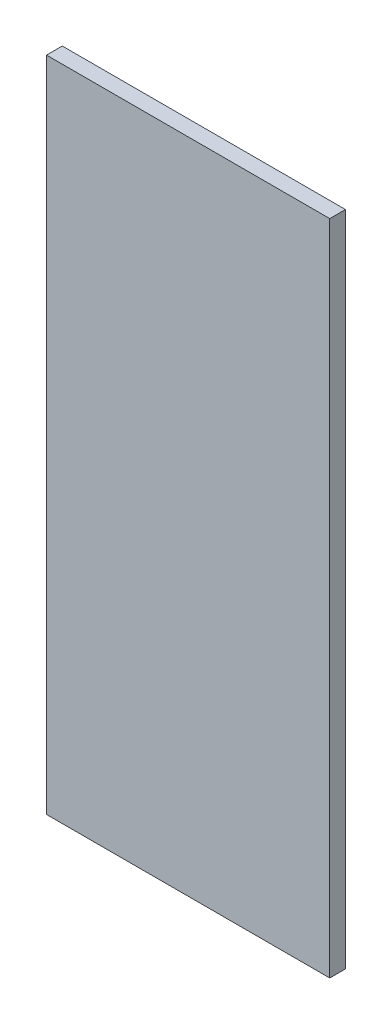
SolidWorks part; units mm, degrees
material "AISI 1020"
ref_plane "Спереди" through (0, 0, 0) normal (0, 0, 1) x (1, 0, 0)
ref_plane "Сверху" through (0, 0, 0) normal (0, 1, 0) x (1, 0, 0)
ref_plane "Справа" through (0, 0, 0) normal (1, 0, 0) x (0, 0, -1)
sketch "Эскиз1" plane through (0, 0, 0) normal (0, 0, 1) x (1, 0, 0)
  line L1 (0, 0) -> (-900, 0)
  line L2 (0, 0) -> (0, 2090)
  line L3 (0, 2090) -> (-900, 2090)
  line L4 (-900, 0) -> (-900, 2090)
  dimension "D1" = 2090
  dimension "D2" = 900
extrude "Бобышка-Вытянуть1" add sketch "Эскиз1" along normal blind 50
